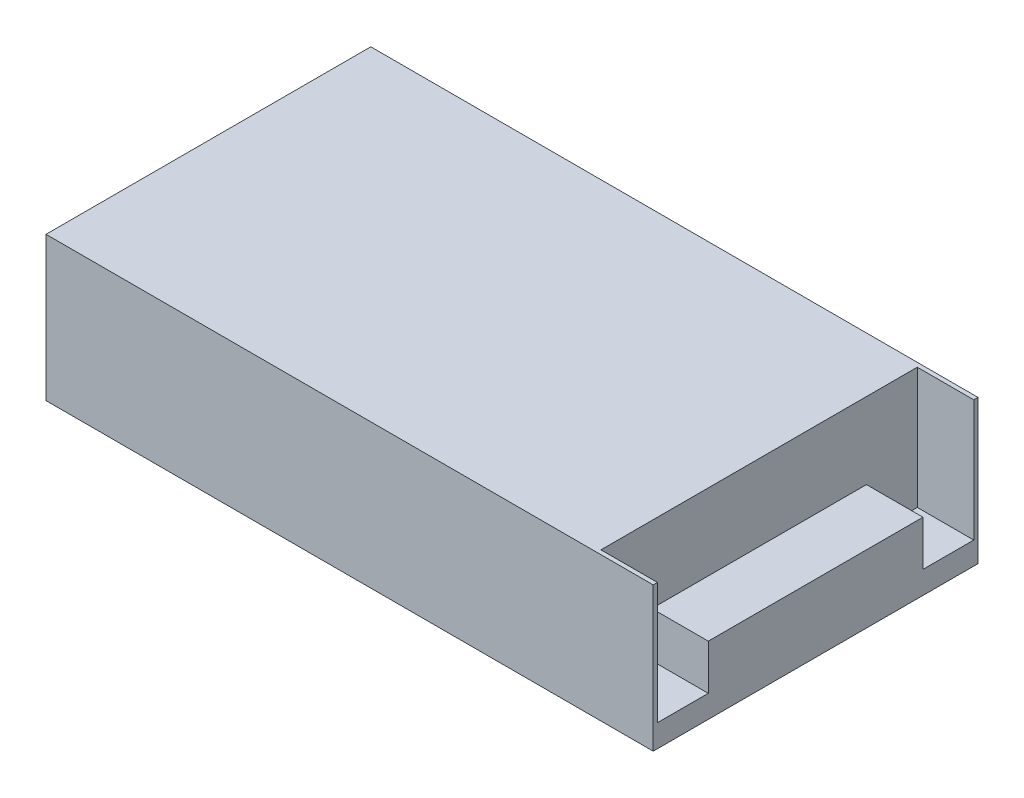
SolidWorks part; units mm, degrees
ref_plane "Спереди" through (0, 0, 0) normal (0, 0, 1) x (1, 0, 0)
ref_plane "Сверху" through (0, 0, 0) normal (0, 1, 0) x (1, 0, 0)
ref_plane "Справа" through (0, 0, 0) normal (1, 0, 0) x (0, 0, -1)
other "Configuration Table"
sketch "Эскиз1" plane through (0, 0, 0) normal (0, 1, 0) x (1, 0, 0)
  line L1 (-107.5, -57.5) -> (107.5, -57.5)
  line L2 (-107.5, -57.5) -> (-107.5, 57.5)
  line L3 (-107.5, 57.5) -> (107.5, 57.5)
  line L4 (107.5, -57.5) -> (107.5, 57.5)
  line L5 (-107.5, -57.5) -> (107.5, 57.5) construction
  line L6 (-107.5, 57.5) -> (107.5, -57.5) construction
  point P0 (0, 0)
  dimension "D1" = 215
  dimension "D2" = 115
extrude "Бобышка-Вытянуть1" add sketch "Эскиз1" along normal blind 51
sketch "Эскиз3" plane through (107.5, 0, 0) normal (1, 0, 0) x (0, 0, -1)
  line L0 (-57.5, 51) -> (57.5, 51) construction
  line L1 (-56, 51) -> (56, 51)
  line L2 (-56, 51) -> (-56, 24)
  line L3 (-38, 24) -> (38, 24)
  line L4 (56, 51) -> (56, 24)
  line L5 (-57.5, 51) -> (-57.5, 0) construction
  line L6 (-57.5, 0) -> (57.5, 0) construction
  line L7 (57.5, 51) -> (57.5, 0) construction
  line L10 (-56, 24) -> (-56, 8)
  line L11 (-56, 8) -> (-38, 8)
  line L12 (-38, 24) -> (-38, 8)
  line L14 (56, 24) -> (56, 8)
  line L15 (56, 8) -> (38, 8)
  line L16 (38, 24) -> (38, 8)
  dimension "D1" = 1.5
  dimension "D2" = 24
  dimension "D3" = 1.5
  dimension "D4" = 8
  dimension "D5" = 18
extrude "Вырез-Вытянуть1" cut sketch "Эскиз3" against normal blind 20
